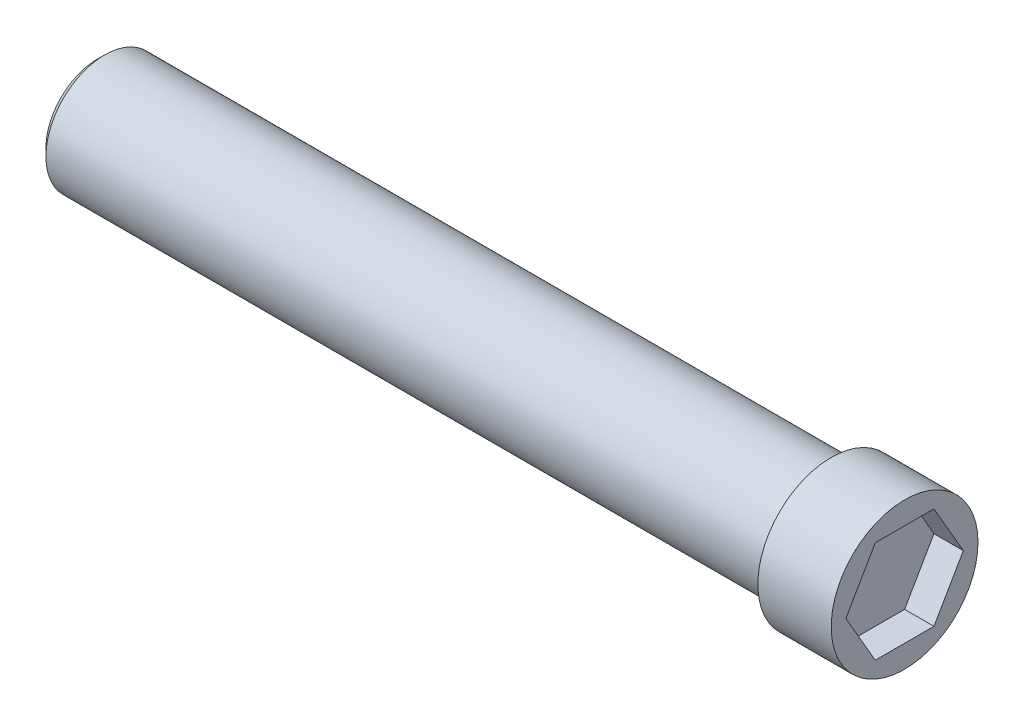
SolidWorks part; units mm, degrees
ref_plane "Alzado" through (0, 0, 0) normal (0, 0, 1) x (1, 0, 0)
ref_plane "Planta" through (0, 0, 0) normal (0, 1, 0) x (1, 0, 0)
ref_plane "Vista lateral" through (0, 0, 0) normal (1, 0, 0) x (0, 0, -1)
sketch "Croquis1" plane through (0, 0, 0) normal (1, 0, 0) x (0, 0, -1)
  circle A0 centre (0, 0) radius 4
  dimension "D1" = 8
extrude "Saliente-Extruir1" add sketch "Croquis1" along normal blind 50
cosmetic thread "Rosca cosmética1" parameters "D2"=7
sketch "Croquis2" plane through (50, 0, 0) normal (1, 0, 0) x (0, 0, -1)
  circle A0 centre (0, 0) radius 5
  dimension "D1" = 10
extrude "Saliente-Extruir2" add sketch "Croquis2" along normal blind 5
sketch "Croquis3" plane through (55, 0, 0) normal (1, 0, 0) x (0, 0, -1)
  line L0 (-5, 0) -> (5, 0) construction
  line L2 (4, 0) -> (2, 3.4641)
  line L3 (2, 3.4641) -> (-2, 3.4641)
  line L4 (-2, 3.4641) -> (-4, 0)
  line L5 (-4, 0) -> (-2, -3.4641)
  line L6 (-2, -3.4641) -> (2, -3.4641)
  line L7 (2, -3.4641) -> (4, 0)
  circle A0 centre (0, 0) radius 5 construction
  circle A1 centre (0, 0) radius 3.4641 construction
  dimension "D1" = 4
  dimension "D2" = 1
extrude "Cortar-Extruir1" cut sketch "Croquis3" against normal blind 2
chamfer "Chaflán1" distance 0.5 angle 45 1 edges at (0, 0, -4)
